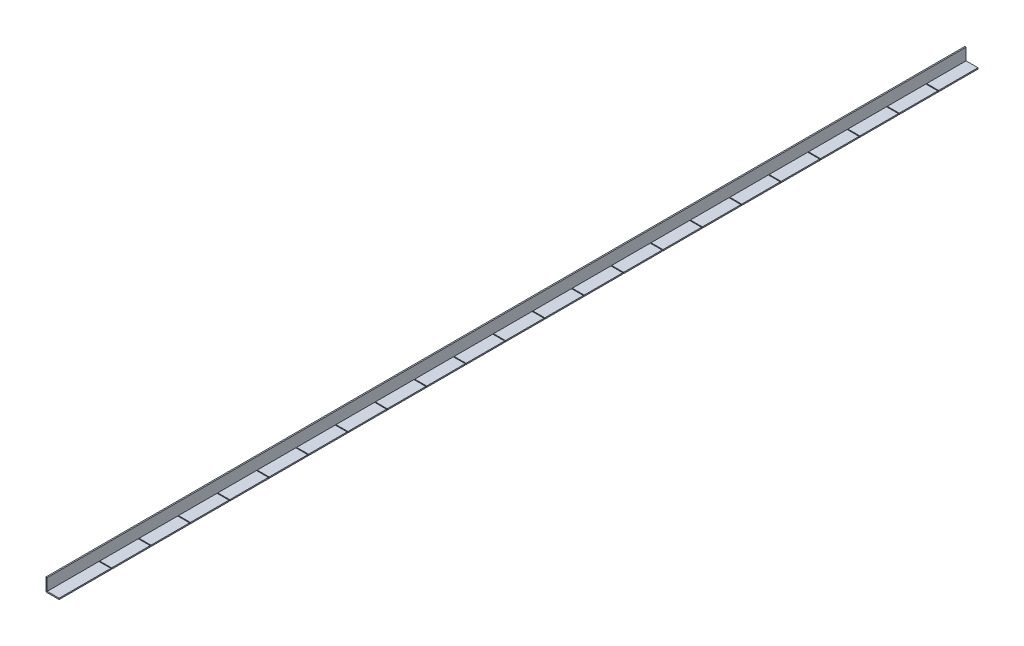
SolidWorks part; units mm, degrees
ref_plane "Front Plane" through (0, 0, 0) normal (0, 0, 1) x (1, 0, 0)
ref_plane "Top Plane" through (0, 0, 0) normal (0, 1, 0) x (1, 0, 0)
ref_plane "Right Plane" through (0, 0, 0) normal (1, 0, 0) x (0, 0, -1)
sketch "Sketch1" plane through (0, 0, 0) normal (0, 0, 1) x (1, 0, 0)
  line L1 (0, 0) -> (50.8, 0)
  line L2 (0, 0) -> (0, 50.8)
  line L3 (0, 50.8) -> (4.7625, 50.8)
  line L4 (50.8, 0) -> (50.8, 4.7625)
  line L7 (50.8, 4.7625) -> (4.7625, 4.7625)
  line L8 (4.7625, 50.8) -> (4.7625, 4.7625)
  dimension "D1" = 50.8
  dimension "D2" = 50.8
  dimension "D3" = 46.0375
  dimension "D4" = 46.0375
extrude "Boss-Extrude1" add sketch "Sketch1" along normal blind 3556
sketch "Sketch2" plane through (4.7625, 0, 0) normal (1, 0, 0) x (0, 0, -1)
  line L0 (-3556, 4.7625) -> (0, 4.7625) construction
  line L1 (-155.575, 4.7625) -> (-152.4, 4.7625)
  line L2 (-155.575, 4.7625) -> (-155.575, -5.2778)
  line L3 (-155.575, -5.2778) -> (-152.4, -5.2778)
  line L4 (-152.4, 4.7625) -> (-152.4, -5.2778)
  dimension "D1" = 3.175
  dimension "D2" = 152.4
extrude "Cut-Extrude1" cut sketch "Sketch2" along normal blind 80
pattern_linear "LPattern1" count 22 spacing 152.4 along (0, 0, 1) of "Cut-Extrude1"
